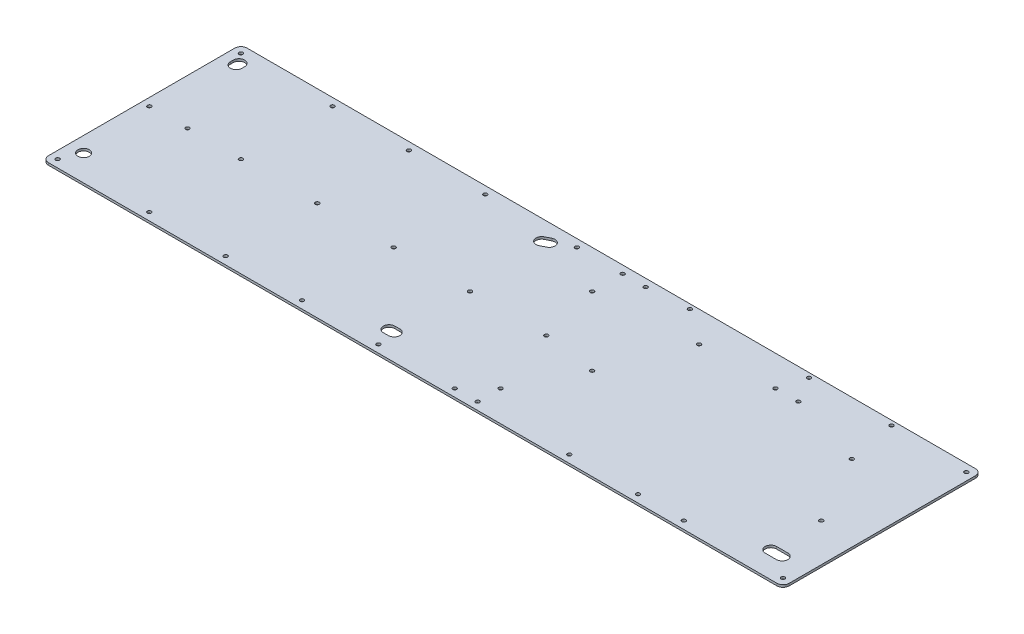
SolidWorks part; units mm, degrees
ref_plane "Front Plane" through (0, 0, 0) normal (0, 0, 1) x (1, 0, 0)
ref_plane "Top Plane" through (0, 0, 0) normal (0, 1, 0) x (1, 0, 0)
ref_plane "Right Plane" through (0, 0, 0) normal (1, 0, 0) x (0, 0, -1)
sketch "Sketch1" plane through (0, 0, 0) normal (0, 1, 0) x (1, 0, 0)
  line L41 (10, 118.7126) -> (10, 116.8884) construction
  line L144 (0, 130) -> (485, 130)
  line L147 (0, 130) -> (0, 0)
  line L150 (0, 0) -> (485, 0)
  line L175 (485, 130) -> (485, 0)
  line L176 (13.75, 118.7126) -> (13.75, 116.8884)
  line L177 (6.25, 118.7126) -> (6.25, 116.8884)
  line L178 (213.3033, 118.6001) -> (209.9889, 116.9437) construction
  line L179 (214.9797, 115.2457) -> (211.6652, 113.5893)
  line L180 (211.627, 121.9546) -> (208.3125, 120.2982)
  line L181 (209.9889, 17) -> (213.3033, 17) construction
  line L182 (209.9889, 20.75) -> (213.3033, 20.75)
  line L183 (209.9889, 13.25) -> (213.3033, 13.25)
  line L184 (467.3766, 17) -> (460, 17) construction
  line L185 (467.3766, 13.25) -> (460, 13.25)
  line L186 (467.3766, 20.75) -> (460, 20.75)
  circle A35 centre (5, 125) radius 1.25
  circle A36 centre (65, 125) radius 1.25
  circle A37 centre (5, 65) radius 1.25
  circle A38 centre (30, 65) radius 1.25
  circle A39 centre (65, 65) radius 1.25
  circle A40 centre (115, 125) radius 1.25
  circle A41 centre (115, 65) radius 1.25
  circle A42 centre (5, 5) radius 1.25
  circle A43 centre (65, 5) radius 1.25
  circle A44 centre (115, 5) radius 1.25
  circle A45 centre (165, 5) radius 1.25
  circle A46 centre (215, 5) radius 1.25
  circle A47 centre (265, 5) radius 1.25
  circle A48 centre (280, 5) radius 1.25
  circle A49 centre (280, 20) radius 1.25
  circle A50 centre (415, 5) radius 1.25
  circle A51 centre (385, 5) radius 1.25
  circle A52 centre (339.9969, 5) radius 1.25
  circle A53 centre (480, 5) radius 1.25
  circle A54 centre (460, 50) radius 1.25
  circle A55 centre (435, 95) radius 1.25
  circle A56 centre (369.9978, 110.0294) radius 1.25
  circle A57 centre (385, 110.0294) radius 1.25
  circle A58 centre (480, 125) radius 1.25
  circle A59 centre (429, 127) radius 1.25
  circle A60 centre (374.95, 127) radius 1.25
  circle A61 centre (300, 60) radius 1.25
  circle A62 centre (265, 65) radius 1.25
  circle A63 centre (255, 105) radius 1.25
  circle A64 centre (320, 110) radius 1.25
  circle A65 centre (297, 127) radius 1.25
  circle A66 centre (270, 125) radius 1.25
  circle A67 centre (255, 125) radius 1.25
  circle A68 centre (215, 65) radius 1.25
  circle A69 centre (165, 65) radius 1.25
  circle A70 centre (165, 125) radius 1.25
  circle A71 centre (215, 125) radius 1.25 construction
  arc A72 (13.75, 118.7126) -> (6.25, 118.7126) centre (10, 118.7126) ccw
  arc A73 (6.25, 116.8884) -> (13.75, 116.8884) centre (10, 116.8884) ccw
  circle A74 centre (10, 17) radius 3.75
  arc A75 (214.9797, 115.2457) -> (211.627, 121.9546) centre (213.3033, 118.6001) ccw
  arc A76 (208.3125, 120.2982) -> (211.6652, 113.5893) centre (209.9889, 116.9437) ccw
  arc A77 (209.9889, 20.75) -> (209.9889, 13.25) centre (209.9889, 17) ccw
  arc A78 (213.3033, 13.25) -> (213.3033, 20.75) centre (213.3033, 17) ccw
  arc A79 (467.3766, 13.25) -> (467.3766, 20.75) centre (467.3766, 17) ccw
  arc A80 (460, 20.75) -> (460, 13.25) centre (460, 17) ccw
  circle A81 centre (225, 125) radius 1.25
  point P80 (10, 117.8005)
  point P87 (211.6461, 117.7719)
  point P94 (211.6461, 17)
  point P101 (463.6883, 17)
  point P110 (0, 0)
  point P111 (211.6461, 13.25)
  dimension "D1" = 2.5
  dimension "D3" = 10
  dimension "D6" = 7.5
  dimension "D2" = 10
  dimension "D4" = 7.5
  dimension "D5" = 10
  dimension "D7" = 17
  dimension "D8" = 7.5
  dimension "D9" = 12.2281
  dimension "D10" = 7.5
  dimension "D11" = 17
  dimension "D12" = 7.5
extrude "Boss-Extrude1" add sketch "Sketch1" against normal blind 1.5 from offset 4 offset against normal yes
fillet "Fillet1" radius 4 4 edges at (485, -4.75, 0) (485, -4.75, -130) (0, -4.75, 0) (0, -4.75, -130)
